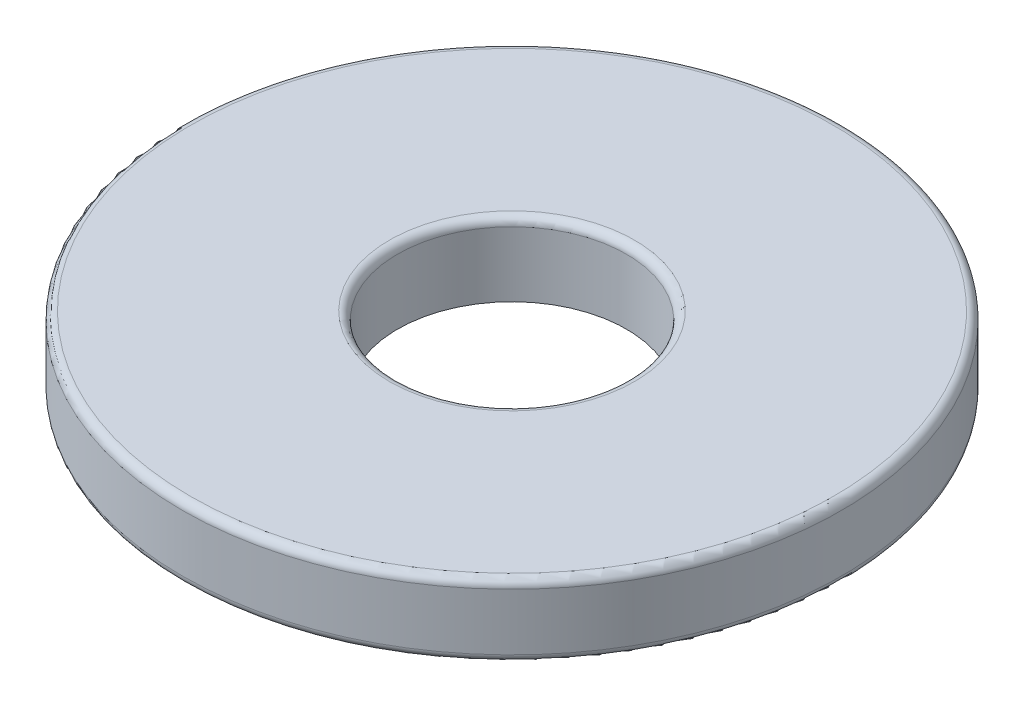
SolidWorks part; units mm, degrees
material "AISI 1020"
ref_plane "Front Plane" through (0, 0, 0) normal (0, 0, 1) x (1, 0, 0)
ref_plane "Top Plane" through (0, 0, 0) normal (0, 1, 0) x (1, 0, 0)
ref_plane "Right Plane" through (0, 0, 0) normal (1, 0, 0) x (0, 0, -1)
sketch "Sketch1" plane through (0, 0, 0) normal (0, 1, 0) x (1, 0, 0)
  circle A0 centre (0, 0) radius 1.7907
  circle A1 centre (0, 0) radius 5.1562
  dimension "D1" = 10.3124
  dimension "D2" = 3.5814
extrude "Boss-Extrude1" add sketch "Sketch1" along normal blind 1.143
fillet "Fillet1" radius 0.127 3 edges at (0, 0, 5.1562) (0, 1.143, 1.7907) (0, 1.143, 5.1562)
